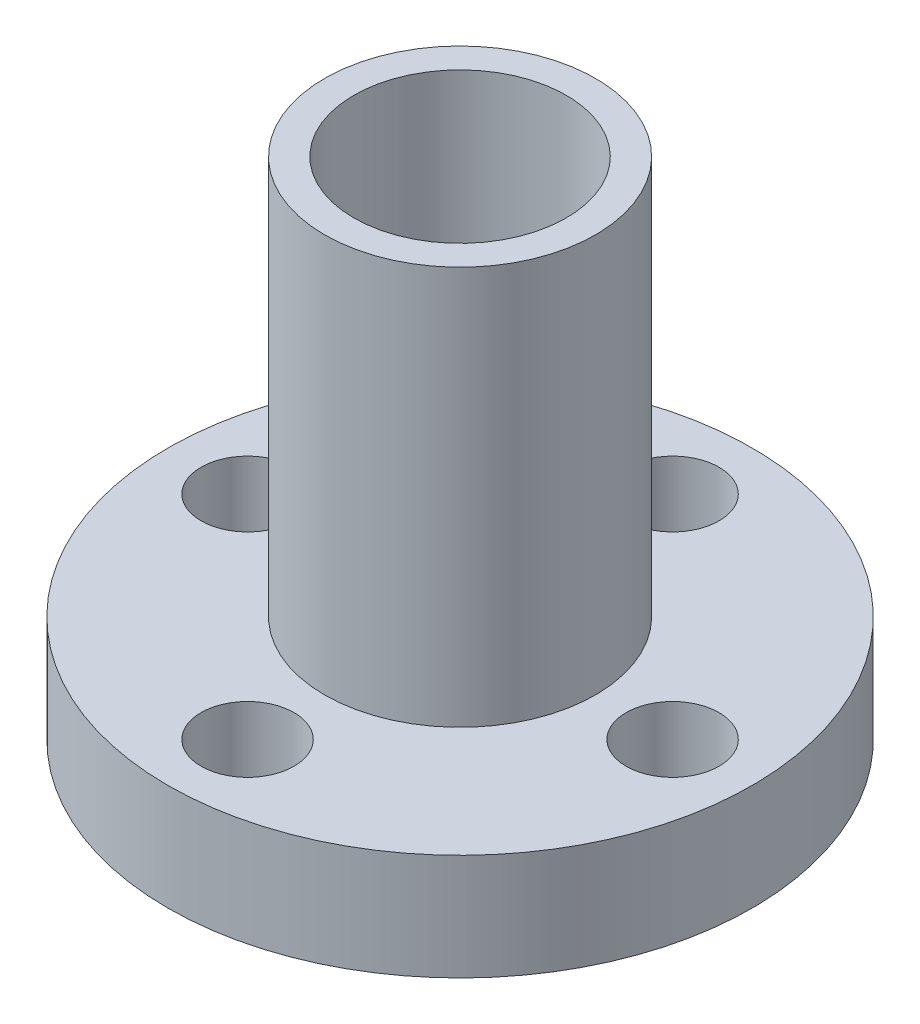
SolidWorks part; units mm, degrees
ref_plane "Front Plane" through (0, 0, 0) normal (0, 0, 1) x (1, 0, 0)
ref_plane "Top Plane" through (0, 0, 0) normal (0, 1, 0) x (1, 0, 0)
ref_plane "Right Plane" through (0, 0, 0) normal (1, 0, 0) x (0, 0, -1)
sketch "Sketch1" plane through (0, 0, 0) normal (0, 1, 0) x (1, 0, 0)
  circle A0 centre (0, 0) radius 11
  dimension "D1" = 22
extrude "Boss-Extrude1" add sketch "Sketch1" along normal blind 4
sketch "Sketch2" plane through (0, 4, 0) normal (0, 1, 0) x (1, 0, 0)
  circle A0 centre (0, 0) radius 5.1
  dimension "D1" = 10.2
extrude "Boss-Extrude2" add sketch "Sketch2" along normal blind 15
sketch "Sketch3" plane through (0, 19, 0) normal (0, 1, 0) x (1, 0, 0)
  circle A0 centre (0, 0) radius 4
  dimension "D1" = 8
extrude "Cut-Extrude1" cut sketch "Sketch3" against normal through all
sketch "Sketch4" plane through (0, 4, 0) normal (0, 1, 0) x (1, 0, 0)
  line L0 (0, -8) -> (0, 8) construction
  line L1 (-8, 0) -> (8, 0) construction
  circle A0 centre (0, 8) radius 1.75
  circle A1 centre (0, -8) radius 1.75
  circle A2 centre (-8, 0) radius 1.75
  circle A3 centre (8, 0) radius 1.75
  point P4 (0, 0)
  point P10 (0, 0)
  dimension "D2" = 3.5
  dimension "D3" = 3.5
  dimension "D5" = 3.5
  dimension "D6" = 3.5
  dimension "D1" = 16
  dimension "D4" = 16
extrude "Cut-Extrude2" cut sketch "Sketch4" against normal through all
